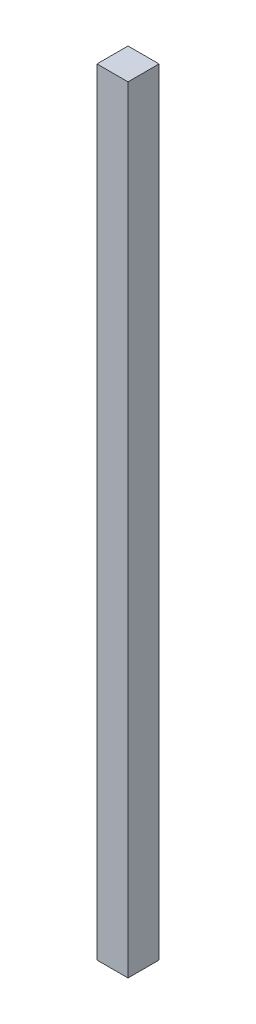
SolidWorks part; units mm, degrees
ref_plane "Спереди" through (0, 0, 0) normal (0, 0, 1) x (1, 0, 0)
ref_plane "Сверху" through (0, 0, 0) normal (0, 1, 0) x (1, 0, 0)
ref_plane "Справа" through (0, 0, 0) normal (1, 0, 0) x (0, 0, -1)
sketch "Эскиз1" plane through (0, 0, 0) normal (0, 1, 0) x (1, 0, 0)
  line L1 (-16.0788, 23.2728) -> (23.9212, 23.2728)
  line L2 (-16.0788, 23.2728) -> (-16.0788, -16.7272)
  line L3 (-16.0788, -16.7272) -> (23.9212, -16.7272)
  line L4 (23.9212, 23.2728) -> (23.9212, -16.7272)
extrude "Бобышка-Вытянуть1" add sketch "Эскиз1" along normal blind 1000
